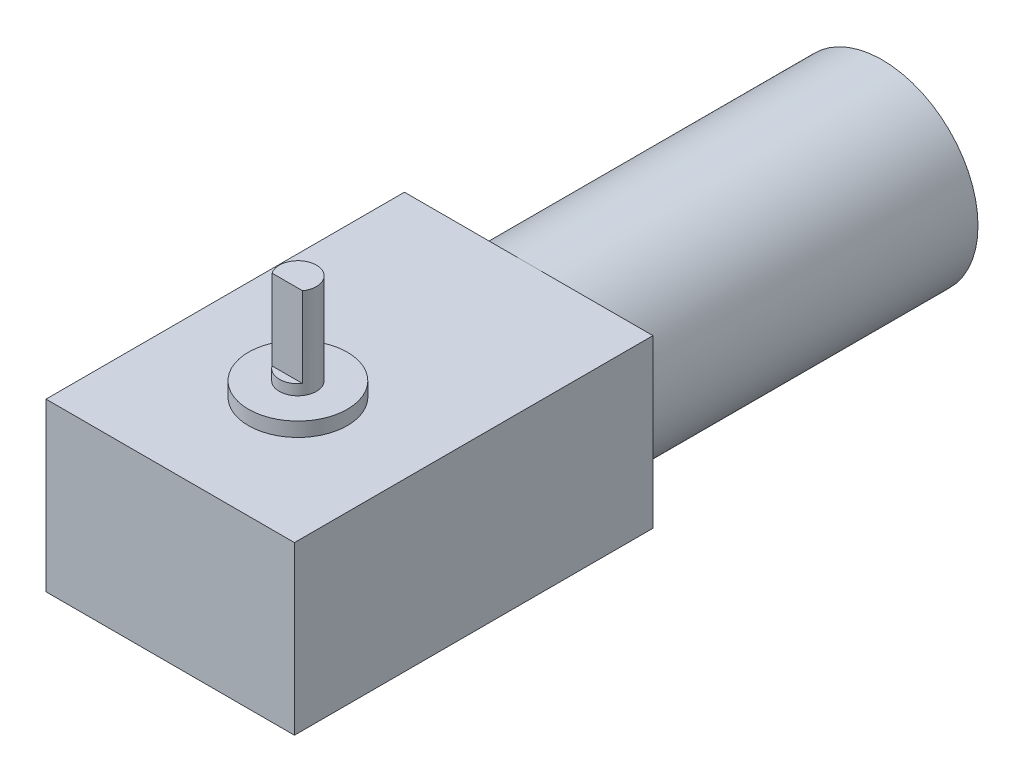
SolidWorks part; units mm, degrees
ref_plane "Płaszczyzna przednia" through (0, 0, 0) normal (0, 0, 1) x (1, 0, 0)
ref_plane "Płaszczyzna górna" through (0, 0, 0) normal (0, 1, 0) x (1, 0, 0)
ref_plane "Płaszczyzna prawa" through (0, 0, 0) normal (1, 0, 0) x (0, 0, -1)
sketch "Szkic1" plane through (0, 0, 0) normal (0, 0, 1) x (1, 0, 0)
  circle A0 centre (0, 0) radius 15.5
  dimension "D1" = 31
extrude "Dodanie-wyciągnięcie1" add sketch "Szkic1" along normal blind 57.2
sketch "Szkic2" plane through (0, 0, 57.2) normal (0, 0, 1) x (1, 0, 0)
  line L1 (-20.1, 15.5) -> (20.1, 15.5)
  line L2 (-20.1, 15.5) -> (-20.1, -11.5)
  line L3 (-20.1, -11.5) -> (20.1, -11.5)
  line L4 (20.1, 15.5) -> (20.1, -11.5)
  circle A0 centre (0, 0) radius 15.5 construction
  circle A1 centre (0, 0) radius 15.5
  circle M6 centre (0, 0) radius 15.5
  dimension "D1" = 27
  dimension "D2" = 40.2
  dimension "D3" = 20.1
extrude "Dodanie-wyciągnięcie2" add sketch "Szkic2" along normal blind 58 contours L2 L3 L1 M6 | L3 M6 | L4 L1 L3 M6
sketch "Szkic3" plane through (0, 15.5, 0) normal (0, 1, 0) x (1, 0, 0)
  circle A0 centre (0, -94.5406) radius 8
extrude "Dodanie-wyciągnięcie3" add sketch "Szkic3" along normal blind 2.3
sketch "Szkic4" plane through (0, 17.8, 0) normal (0, 1, 0) x (1, 0, 0)
  circle A0 centre (0, -94.5406) radius 3
  dimension "D1" = 6
extrude "Dodanie-wyciągnięcie4" add sketch "Szkic4" along normal blind 14.7
sketch "Szkic5" plane through (0, 32.5, 0) normal (0, 1, 0) x (1, 0, 0)
  line L1 (-3.2179, -97.5406) -> (3.5761, -97.5406)
  line L2 (-3.2179, -97.5406) -> (-3.2179, -96.2565)
  line L3 (-3.2179, -96.2565) -> (3.5761, -96.2565)
  line L4 (3.5761, -97.5406) -> (3.5761, -96.2565)
  circle A0 centre (0, -94.5406) radius 3 construction
extrude "Wytnij-wyciągnięcie1" cut sketch "Szkic5" against normal blind 13
sketch "Szkic6" plane through (0, -11.5, 0) normal (0, -1, 0) x (1, 0, 0)
  line L0 (0, 115.2) -> (0, -12.4582) construction
  line L1 (-20.1, 115.2) -> (20.1, 115.2) construction
  line L2 (27.3934, 86.2) -> (-35.6544, 86.2) construction
  circle A0 centre (14.1, 106.2) radius 2
  circle A1 centre (14.1, 66.2) radius 2
  circle A2 centre (-14.1, 66.2) radius 2
  circle A3 centre (-14.1, 106.2) radius 2
  dimension "D2" = 4
  dimension "D3" = 20
  dimension "D1" = 14.1
  dimension "D4" = 29
extrude "Wytnij-wyciągnięcie2" cut sketch "Szkic6" against normal blind 7
sketch "Szkic7" plane through (0, -11.5, 0) normal (0, -1, 0) x (1, 0, 0)
  line L0 (-20.1, 115.2) -> (20.1, 115.2) construction
  line L1 (-20.1, 115.2) -> (-20.1, 57.2) construction
  circle A0 centre (0, 95.2) radius 9.25
  dimension "D1" = 18.5
  dimension "D2" = 20
  dimension "D3" = 20.1
extrude "Dodanie-wyciągnięcie5" add sketch "Szkic7" along normal blind 4.5
sketch "Szkic8" plane through (0, -11.5, 0) normal (0, -1, 0) x (1, 0, 0)
  circle A0 centre (-14.1, 106.2) radius 2 construction
  circle A1 centre (-14.1, 66.2) radius 2 construction
  circle A2 centre (14.1, 66.2) radius 2 construction
  circle A3 centre (14.1, 106.2) radius 2 construction
  circle A4 centre (-14.1, 106.2) radius 2
  circle A5 centre (-14.1, 66.2) radius 2
  circle A6 centre (14.1, 66.2) radius 2
  circle A7 centre (14.1, 106.2) radius 2
  circle A8 centre (14.1, 106.2) radius 3.5
  circle A9 centre (14.1, 66.2) radius 3.5
  circle A10 centre (-14.1, 66.2) radius 3.5
  circle A11 centre (-14.1, 106.2) radius 3.5
  dimension "D1" = 1.5
extrude "Dodanie-wyciągnięcie6" add sketch "Szkic8" along normal blind 2
